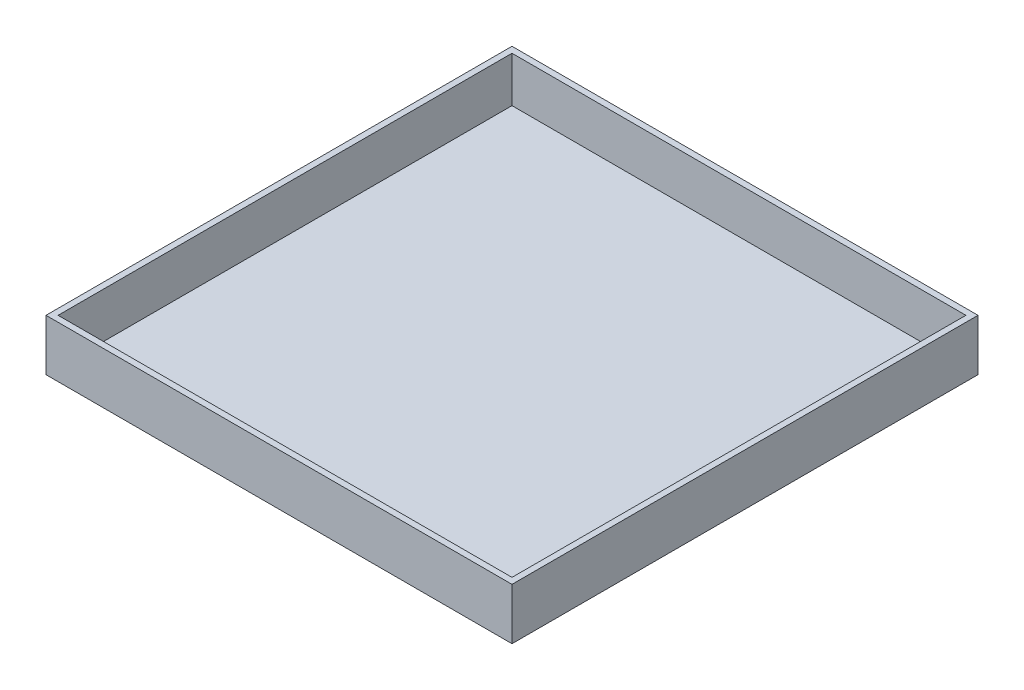
SolidWorks part; units mm, degrees
material "Polyethylene Cross-Linked"
ref_plane "Front Plane" through (0, 0, 0) normal (0, 0, 1) x (1, 0, 0)
ref_plane "Top Plane" through (0, 0, 0) normal (0, 1, 0) x (1, 0, 0)
ref_plane "Right Plane" through (0, 0, 0) normal (1, 0, 0) x (0, 0, -1)
sketch "Sketch1" plane through (0, 0, 0) normal (0, 1, 0) x (1, 0, 0)
  line L1 (75, -75) -> (-75, -75)
  line L2 (75, -75) -> (75, 75)
  line L3 (75, 75) -> (-75, 75)
  line L4 (-75, -75) -> (-75, 75)
  line L5 (75, -75) -> (-75, 75) construction
  line L6 (75, 75) -> (-75, -75) construction
  point P0 (0, 0)
  dimension "D1" = 150
  dimension "D2" = 150
extrude "Boss-Extrude1" add sketch "Sketch1" along normal blind 2
sketch "Sketch2" plane through (0, 2, 0) normal (0, 1, 0) x (1, 0, 0)
  line L0 (-75, 75) -> (-75, -75) construction
  line L1 (77, -77) -> (-77, -77)
  line L2 (77, -77) -> (77, 77)
  line L3 (77, 77) -> (-77, 77)
  line L4 (-77, -77) -> (-77, 77)
  line L5 (77, -77) -> (-77, 77) construction
  line L6 (77, 77) -> (-77, -77) construction
  line L7 (-75, -75) -> (75, -75) construction
  point P0 (0, 0)
  dimension "D1" = 2
  dimension "D2" = 2
extrude "Boss-Extrude2" add sketch "Sketch2" against normal blind 2
sketch "Sketch3" plane through (0, 2, 0) normal (0, 1, 0) x (1, 0, 0)
  line L1 (-77, -77) -> (77, -77)
  line L2 (-77, -77) -> (-77, 77)
  line L3 (-77, 77) -> (77, 77)
  line L4 (77, -77) -> (77, 77)
  line L5 (-77, -77) -> (77, 77) construction
  line L6 (-77, 77) -> (77, -77) construction
  line L7 (-75, -75) -> (75, -75)
  line L8 (-75, -75) -> (-75, 75)
  line L9 (-75, 75) -> (75, 75)
  line L10 (75, -75) -> (75, 75)
  line L11 (-75, -75) -> (75, 75) construction
  line L12 (-75, 75) -> (75, -75) construction
  point P0 (0, 0)
  point P7 (0, 0)
  point P12 (-77, 0)
  dimension "D1" = 2
extrude "Boss-Extrude3" add sketch "Sketch3" along normal blind 15
